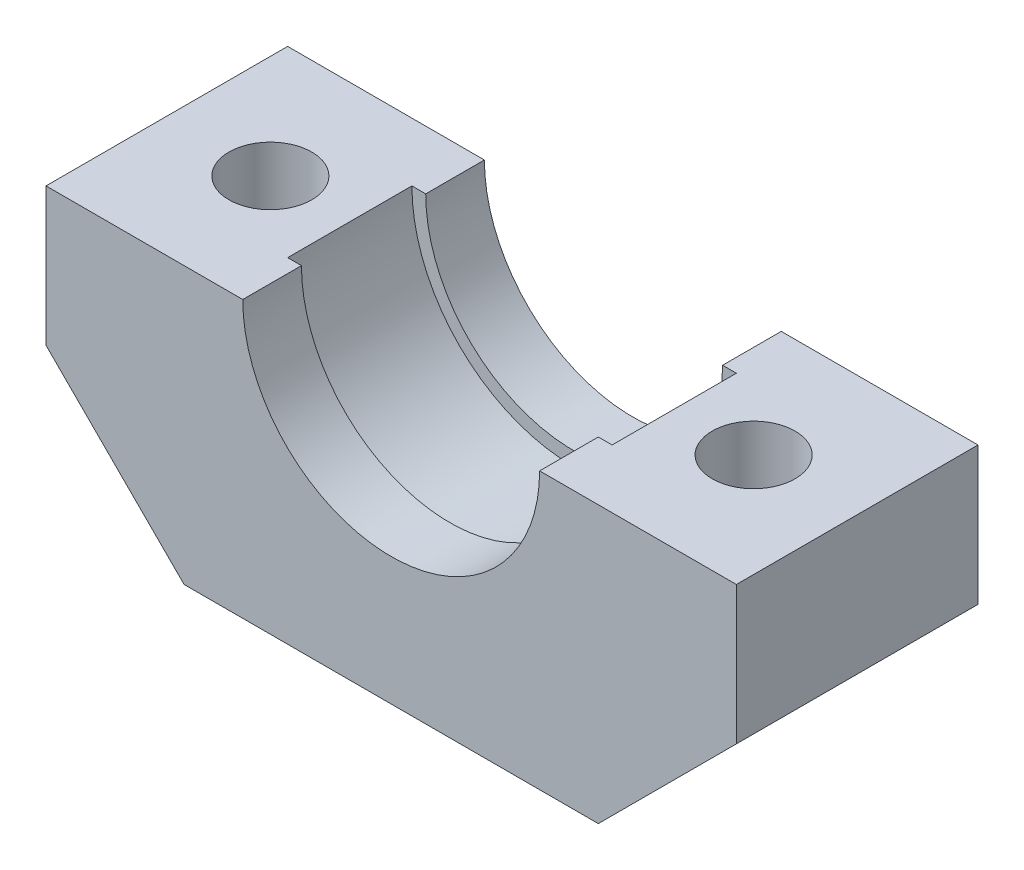
SolidWorks part; units mm, degrees
ref_plane "前视基准面" through (0, 0, 0) normal (0, 0, 1) x (1, 0, 0)
ref_plane "上视基准面" through (0, 0, 0) normal (0, 1, 0) x (1, 0, 0)
ref_plane "右视基准面" through (0, 0, 0) normal (1, 0, 0) x (0, 0, -1)
sketch "草图2" plane through (0, 0, 0) normal (0, 0, 1) x (1, 0, 0)
  line L0 (0, 0) -> (0, -20)
  line L1 (0, -20) -> (20, -40)
  line L2 (20, -40) -> (80, -40)
  line L3 (28.5, 0) -> (0, 0)
  line L4 (100, -20) -> (100, 0)
  line L5 (100, 0) -> (71.5, 0)
  line L7 (80, -40) -> (100, -20)
  line L8 (50, -40) -> (50, 50000) construction
  arc A0 (28.5, 0) -> (71.5, 0) centre (50, 0) ccw
  dimension "D1" = 43
  dimension "D2" = 100
  dimension "D3" = 28.5
  dimension "D4" = 28.5
  dimension "D5" = 20
  dimension "D6" = 20
  dimension "D7" = 60
  dimension "D8" = 40
extrude "凸台-拉伸1" add sketch "草图2" along normal mid plane 35
sketch "草图3" plane through (0, 0, 0) normal (0, 0, 1) x (1, 0, 0)
  circle A0 centre (50, 0) radius 23.5
  dimension "D1" = 47
extrude "切除-拉伸1" cut sketch "草图3" against normal mid plane 18
hole_wizard "M14 螺纹孔1" positions "草图5" profile "草图4" tap size "M14" standard "Gb"
sketch "草图5" plane through (0, 0, 0) normal (0, 1, 0) x (1, 0, 0)
  line L0 (0, -17.5) -> (0, 17.5) construction
  line L1 (100, -17.5) -> (100, 17.5) construction
  line L2 (28.5, 17.5) -> (0, 17.5) construction
  line L3 (100, 17.5) -> (71.5, 17.5) construction
  point P0 (15, 0)
  point P2 (85, 0)
  point P11 (85.75, 17.5)
  dimension "D1" = 15
  dimension "D2" = 15
  dimension "D3" = 17.5
  dimension "D4" = 17.5
sketch "草图4" plane through (15, 0, 0) normal (1, 0, 0) x (0, 0, 1)
  line L0 (0, 0) -> (0, 23.6052)
  line L1 (0, 23.6052) -> (6, 20)
  line L2 (6, 20) -> (6, 0)
  line L5 (6, 0) -> (0, 0)
  line L10 (0, 23.6052) -> (-6, 20) construction
  line L11 (0, -6.35) -> (0, 107.95) construction
  dimension "螺纹孔钻头直径" = 12
  dimension "螺纹孔钻头深度" = 20
  dimension "导头角度" = 118
cosmetic thread "孔螺蚊线1" parameters "D1"=20, "D2"=14
cosmetic thread "孔螺蚊线2" parameters "D1"=20, "D2"=14
hole_wizard "M6 螺纹孔1" positions "草图7" profile "草图6" tap size "M6" standard "Gb"
sketch "草图7" plane through (60, -60, 0) normal (0.7071, -0.7071, 0) x (-0.7071, -0.7071, 0)
  line L0 (-28.2843, 17.5) -> (-56.5685, 17.5) construction
  line L1 (-28.2843, -17.5) -> (-28.2843, 17.5) construction
  point P0 (-33.2843, 0)
  dimension "D1" = 17.5
  dimension "D2" = 5
cosmetic thread "孔螺蚊线3" parameters "D1"=10, "D2"=6
sketch "草图6" plane through (83.5355, -36.4645, 0) normal (0, 0, 1) x (0.7071, 0.7071, 0)
  line L0 (0, 0) -> (0, 16.5022)
  line L1 (0, 16.5022) -> (2.5, 15)
  line L2 (2.5, 15) -> (2.5, 0)
  line L5 (2.5, 0) -> (0, 0)
  line L10 (0, 16.5022) -> (-2.5, 15) construction
  line L11 (0, -6.35) -> (0, 107.95) construction
  dimension "螺纹孔钻头直径" = 5
  dimension "螺纹孔钻头深度" = 15
  dimension "导头角度" = 118
ref_plane "基准面1" through (52.9289, -52.9289, 0) normal (0.7071, -0.7071, 0) x (-0.7071, -0.7071, 0)
sketch "草图8" plane through (52.9289, -52.9289, 0) normal (0.7071, -0.7071, 0) x (-0.7071, -0.7071, 0)
  circle A0 centre (-33.2843, 0) radius 2.5
  dimension "D1" = 5
extrude "切除-拉伸2" cut sketch "草图8" against normal through all
ref_plane "基准面2" through (50, 0, 0) normal (-1, 0, 0) x (0, 0, 1)
